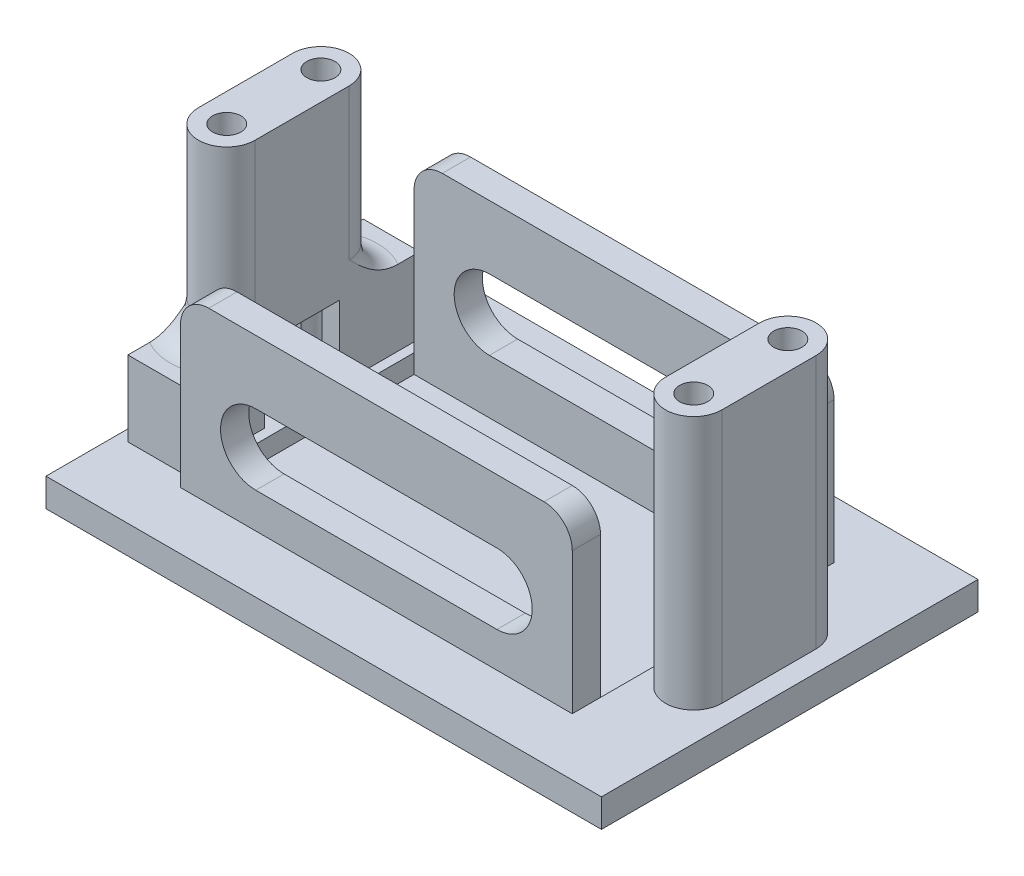
SolidWorks part; units mm, degrees
ref_plane "前视基准面" through (0, 0, 0) normal (0, 0, 1) x (1, 0, 0)
ref_plane "上视基准面" through (0, 0, 0) normal (0, 1, 0) x (1, 0, 0)
ref_plane "右视基准面" through (0, 0, 0) normal (1, 0, 0) x (0, 0, -1)
other "Configuration Table"
sketch "草图1" plane through (0, 0, 0) normal (0, 1, 0) x (1, 0, 0)
  line L0 (27.5, 0) -> (22.3, 0) construction
  line L1 (-27.5, 20) -> (27.5, 20)
  line L2 (-27.5, 20) -> (-27.5, -20)
  line L3 (-27.5, -20) -> (27.5, -20)
  line L4 (27.5, 20) -> (27.5, -20)
  line L5 (-27.5, 20) -> (27.5, -20) construction
  line L6 (-27.5, -20) -> (27.5, 20) construction
  line L7 (22.3, 0) -> (22.3, 5) construction
  circle A0 centre (-12.5, 0) radius 10 construction
  circle A1 centre (22.3, 5) radius 1.5
  circle A2 centre (22.3, -5) radius 1.5
  point P0 (0, 0)
  point P6 (-12.5, 0)
  dimension "D4" = 20
  dimension "D7" = 3
  dimension "D1" = 40
  dimension "D2" = 55
  dimension "D3" = 40
  dimension "D5" = 5.2
  dimension "D6" = 5
extrude "凸台-拉伸1" add sketch "草图1" along normal blind 3
sketch "草图2" plane through (-27.5, 0, 0) normal (-1, 0, 0) x (0, 0, 1)
  line L4 (-20, 0) -> (20, 0)
  line L5 (20, 0) -> (20, 3)
  line L6 (20, 3) -> (-20, 3)
  line L7 (-20, 3) -> (-20, 0)
  line L8 (-20, 0) -> (20, 0)
  line L9 (20, 0) -> (20, 3)
  line L10 (20, 3) -> (-20, 3)
  line L11 (-20, 3) -> (-20, 0)
  dimension "D1" = 0
extrude "凸台-拉伸2" add sketch "草图2" along normal blind 4
sketch "草图3" plane through (0, 0, 0) normal (0, -1, 0) x (1, 0, 0)
  circle A0 centre (-27.3, 5) radius 1.5
  circle A1 centre (-27.3, -5) radius 1.5
extrude "切除-拉伸1" cut sketch "草图3" against normal up to next
sketch "草图4" plane through (0, 0, 0) normal (0, -1, 0) x (1, 0, 0)
  circle A0 centre (-12.5, 0) radius 10.5
  dimension "D1" = 21
extrude "凸台-拉伸3" add sketch "草图4" along normal blind 5
sketch "草图5" plane through (0, 0, 0) normal (0, -1, 0) x (1, 0, 0)
  line L1 (17.3071, 9.9071) -> (-22.3071, 9.9071) construction
  line L2 (17.3071, 9.9071) -> (17.3071, -9.9071) construction
  line L3 (17.3071, -9.9071) -> (-22.3071, -9.9071) construction
  line L4 (-22.3071, 9.9071) -> (-22.3071, -9.9071) construction
  line L8 (18.3071, 10.9071) -> (-23.3071, 10.9071)
  line L9 (-23.3071, 10.9071) -> (-23.3071, -10.9071)
  line L10 (18.3071, -10.9071) -> (-23.3071, -10.9071)
  line L11 (18.3071, 10.9071) -> (18.3071, -10.9071)
  arc A0 (17.6, 9.2) -> (16.6, 10.2) centre (16.6, 9.2) ccw construction
  arc A1 (-22.6, -9.2) -> (-21.6, -10.2) centre (-21.6, -9.2) ccw construction
  dimension "D1" = 1
extrude "切除-拉伸4" cut sketch "草图5" against normal up to next from offset 1 offset against normal yes
sketch "草图6" plane through (0, 3, 0) normal (0, 1, 0) x (1, 0, 0)
  line L0 (-30.3, -5) -> (-30.3, 5)
  line L1 (-24.3, -5) -> (-24.3, 5)
  line L2 (19.3, -5) -> (19.3, 5)
  line L3 (25.3, -5) -> (25.3, 5)
  circle A0 centre (22.3, 5) radius 1.5
  circle A1 centre (22.3, -5) radius 1.5
  circle A2 centre (-27.3, -5) radius 1.5
  circle A3 centre (-27.3, 5) radius 1.5
  arc A4 (-30.3, -5) -> (-24.3, -5) centre (-27.3, -5) ccw
  arc A5 (-24.3, 5) -> (-30.3, 5) centre (-27.3, 5) ccw
  arc A6 (19.3, -5) -> (25.3, -5) centre (22.3, -5) ccw
  arc A7 (25.3, 5) -> (19.3, 5) centre (22.3, 5) ccw
  dimension "D1" = 6
  dimension "D2" = 6
  dimension "D3" = 6
  dimension "D4" = 6
extrude "凸台-拉伸5" add sketch "草图6" along normal blind 27
sketch "草图7" plane through (0, 3, 0) normal (0, 1, 0) x (1, 0, 0)
  line L0 (-30.3, 0) -> (-24.3, 0) construction
  line L1 (-30.3, 5) -> (-30.3, -5) construction
  line L2 (-24.3, -5) -> (-24.3, 5) construction
  line L4 (-30.3, -12.5) -> (-24.3, -12.5)
  line L5 (-30.3, -12.5) -> (-30.3, 12.5)
  line L6 (-30.3, 12.5) -> (-24.3, 12.5)
  line L7 (-24.3, -12.5) -> (-24.3, 12.5)
  line L8 (-30.3, -12.5) -> (-24.3, 12.5) construction
  line L9 (-30.3, 12.5) -> (-24.3, -12.5) construction
  circle A0 centre (-27.3, -5) radius 1.5
  circle A1 centre (-27.3, 5) radius 1.5
  point P6 (-27.3, 0)
  dimension "D1" = 25
extrude "凸台-拉伸6" add sketch "草图7" along normal blind 8
sketch "草图8" plane through (-30.3, 0, 0) normal (-1, 0, 0) x (0, 0, 1)
  line L0 (0, 3) -> (0, 6.9) construction
  line L1 (20, 3) -> (-20, 3) construction
  line L3 (-4, 10.8) -> (4, 10.8)
  line L4 (-4, 10.8) -> (-4, 3)
  line L5 (-4, 3) -> (4, 3)
  line L6 (4, 10.8) -> (4, 3)
  line L7 (-4, 10.8) -> (4, 3) construction
  line L8 (-4, 3) -> (4, 10.8) construction
  dimension "D1" = 8
extrude "切除-拉伸5" cut sketch "草图8" against normal up to next
fillet "圆角1" radius 3 1 edges at (-27.3, 11, 8)
fillet "圆角2" radius 3 1 edges at (-27.3, 11, -8)
sketch "草图9" plane through (0, -5, 0) normal (0, -1, 0) x (1, 0, 0)
  circle A0 centre (-12.5, 0) radius 10.5
extrude "切除-拉伸6" cut sketch "草图9" against normal up to surface (5 mm away) up to face at (-12.5, 0, 10.5)
sketch "草图10" plane through (0, 3, 0) normal (0, 1, 0) x (1, 0, 0)
  line L1 (-23.3071, 10.9071) -> (18.3071, 10.9071)
  line L2 (-23.3071, 10.9071) -> (-23.3071, 13.9071)
  line L3 (-23.3071, 13.9071) -> (18.3071, 13.9071)
  line L4 (18.3071, 10.9071) -> (18.3071, 13.9071)
  line L5 (-23.3071, -10.9071) -> (18.3071, -10.9071)
  line L6 (-23.3071, -10.9071) -> (-23.3071, -13.9071)
  line L7 (-23.3071, -13.9071) -> (18.3071, -13.9071)
  line L8 (18.3071, -10.9071) -> (18.3071, -13.9071)
  dimension "D1" = 3
  dimension "D2" = 3
extrude "凸台-拉伸7" add sketch "草图10" along normal blind 18 contours L2 L1 L4 L3 | L6 L5 L8 L7
fillet "圆角3" radius 3 4 edges at (-23.3071, 21, -12.4071) (-23.3071, 21, 12.4071) (18.3071, 21, -12.4071) (18.3071, 21, 12.4071)
sketch "草图11" plane through (0, 0, 13.9071) normal (0, 0, 1) x (1, 0, 0)
  line L0 (-15.3071, 10.5) -> (10.3071, 10.5) construction
  line L1 (-23.3071, 18) -> (-23.3071, 3) construction
  line L2 (18.3071, 18) -> (18.3071, 3) construction
  line L3 (-15.3071, 10.5) -> (10.3071, 10.5) construction
  line L4 (-15.3071, 14.2455) -> (10.3071, 14.2455)
  line L5 (-15.3071, 6.7545) -> (10.3071, 6.7545)
  arc A0 (-15.3071, 14.2455) -> (-15.3071, 6.7545) centre (-15.3071, 10.5) ccw
  arc A1 (10.3071, 6.7545) -> (10.3071, 14.2455) centre (10.3071, 10.5) ccw
  point P6 (-2.5, 10.5)
  dimension "D1" = 8
  dimension "D2" = 8
extrude "切除-拉伸7" cut sketch "草图11" against normal up to surface (27.8142 mm away) up to face at (-2.5, 14.2071, -13.9071)
